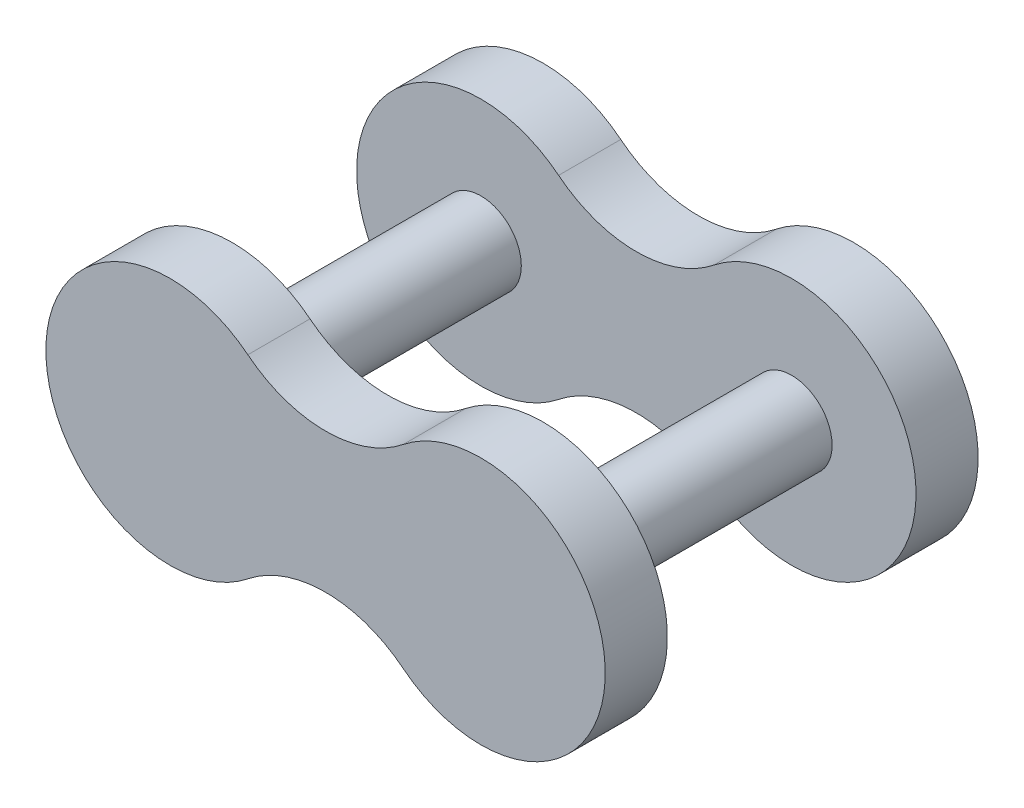
SolidWorks part; units mm, degrees
material "Copper"
ref_plane "Front Plane" through (0, 0, 0) normal (0, 0, 1) x (1, 0, 0)
ref_plane "Top Plane" through (0, 0, 0) normal (0, 1, 0) x (1, 0, 0)
ref_plane "Right Plane" through (0, 0, 0) normal (1, 0, 0) x (0, 0, -1)
sketch "Sketch1" plane through (0, 0, 0) normal (0, 0, 1) x (1, 0, 0)
  line L0 (0, 0) -> (0, 2.047) construction
  line L1 (0, 0) -> (2.1642, 0) construction
  circle A0 centre (3.175, 0) radius 0.8255
  circle A1 centre (-3.175, 0) radius 0.8255
  dimension "D1" = 1.651
  dimension "D2" = 6.35
extrude "Boss-Extrude1" add sketch "Sketch1" along normal mid plane 5.08
sketch "Sketch2" plane through (0, 0, 2.54) normal (0, 0, 1) x (1, 0, 0)
  line L0 (0, 0) -> (0, 2.4346) construction
  line L1 (0, 0) -> (3.175, 0) construction
  arc A0 (1.5875, -1.9828) -> (1.5875, 1.9828) centre (3.175, 0) ccw
  arc A1 (-1.5875, 1.9828) -> (-1.5875, -1.9828) centre (-3.175, 0) ccw
  arc A2 (-1.5875, 1.9828) -> (1.5875, 1.9828) centre (0, 3.9656) ccw
  arc A3 (1.5875, -1.9828) -> (-1.5875, -1.9828) centre (0, -3.9656) ccw
  dimension "D1" = 5.08
extrude "Boss-Extrude2" add sketch "Sketch2" along normal blind 1.27
mirror "Mirror1" about plane through (0, 0, 0) normal (0, 0, 1) of "Boss-Extrude2"
